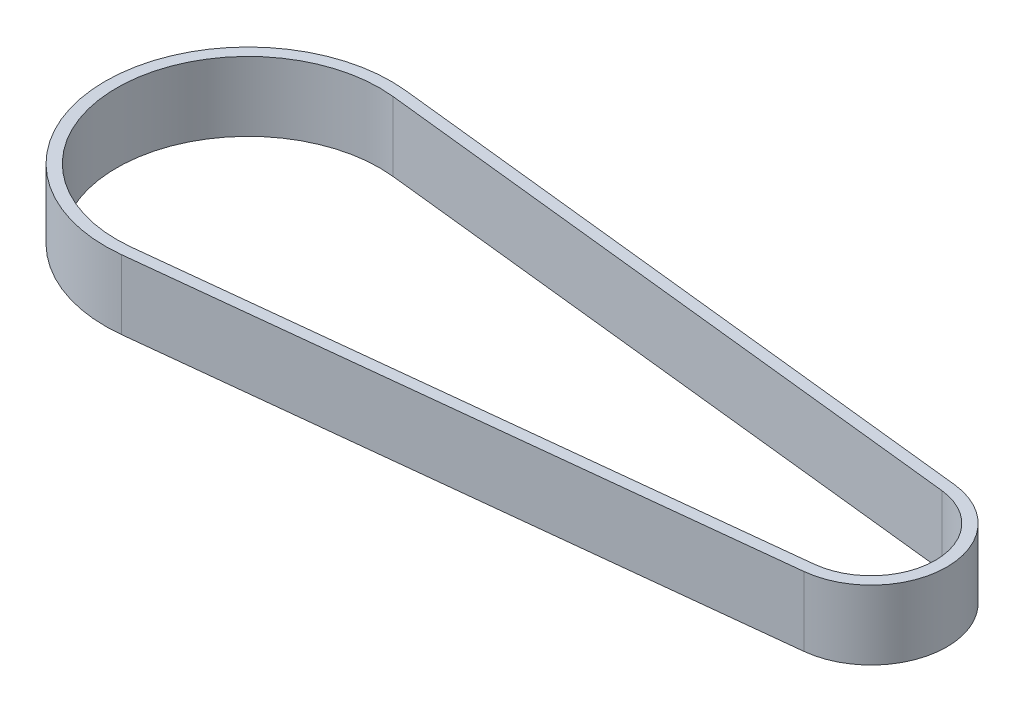
SolidWorks part; units mm, degrees
ref_plane "Front Plane" through (0, 0, 0) normal (0, 0, 1) x (1, 0, 0)
ref_plane "Top Plane" through (0, 0, 0) normal (0, 1, 0) x (1, 0, 0)
ref_plane "Right Plane" through (0, 0, 0) normal (1, 0, 0) x (0, 0, -1)
sketch "Sketch1" plane through (0, 0, 0) normal (0, 1, 0) x (1, 0, 0)
  line L0 (-44.2539, 0) -> (44.2539, 0) construction
  line L1 (-50.5335, -11.3234) -> (2.8371, -5.5275)
  line L2 (2.8371, 5.5275) -> (-50.5335, 11.3234)
  line L3 (-50.4255, -12.3176) -> (2.9451, -6.5217)
  line L4 (2.9451, 6.5217) -> (-50.4255, 12.3176)
  arc A0 (-50.5335, 11.3234) -> (-50.5335, -11.3234) centre (-51.7632, 0) ccw
  arc A1 (2.8371, -5.5275) -> (2.8371, 5.5275) centre (2.2368, 0) ccw
  arc A2 (2.9451, -6.5217) -> (2.9451, 6.5217) centre (2.2368, 0) ccw
  arc A3 (-50.4255, 12.3176) -> (-50.4255, -12.3176) centre (-51.7632, 0) ccw
  dimension "D1" = 22.78
  dimension "D2" = 11.12
  dimension "D3" = 54
  dimension "D4" = 1
extrude "Boss-Extrude1" add sketch "Sketch1" along normal blind 6
